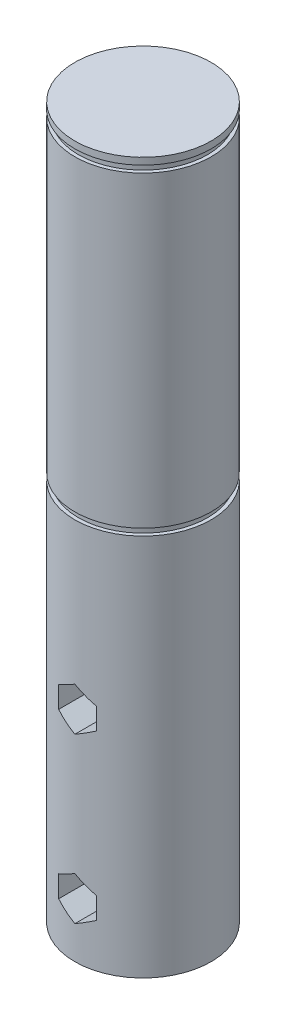
SolidWorks part; units mm, degrees
material "延性铁"
ref_plane "前视基准面" through (0, 0, 0) normal (0, 0, 1) x (1, 0, 0)
ref_plane "上视基准面" through (0, 0, 0) normal (0, 1, 0) x (1, 0, 0)
ref_plane "右视基准面" through (0, 0, 0) normal (1, 0, 0) x (0, 0, -1)
sketch "草图1" plane through (0, 0, 0) normal (0, 1, 0) x (1, 0, 0)
  circle A0 centre (5.9, 0) radius 9.975
  dimension "D1" = 19.95
extrude "凸台-拉伸1" add sketch "草图1" along normal blind 40
ref_plane "基准面1" through (0, 20, 0) normal (0, -1, 0) x (-1, 0, 0)
sketch "草图5" plane through (0, 40, 0) normal (0, 1, 0) x (1, 0, 0)
  circle A0 centre (5.9, 0) radius 9.975
  dimension "D1" = 19.95
extrude "16mm 铰链间距" add sketch "草图5" along normal blind 16
sketch "草图6" plane through (0, 56, 0) normal (0, 1, 0) x (1, 0, 0)
  circle A0 centre (5.9, 0) radius 9.45
  circle A1 centre (5.9, 0) radius 9.975 construction
  dimension "D1" = 18.9
extrude "卡簧1" add sketch "草图6" along normal blind 1
sketch "草图7" plane through (0, 57, 0) normal (0, 1, 0) x (1, 0, 0)
  circle A0 centre (5.9, 0) radius 9.975
  dimension "D1" = 19.95
extrude "凸台-拉伸4" add sketch "草图7" along normal blind 45
sketch "草图8" plane through (0, 102, 0) normal (0, 1, 0) x (1, 0, 0)
  circle A0 centre (5.9, 0) radius 9.45
  dimension "D1" = 18.9
extrude "卡簧2" add sketch "草图8" along normal blind 1
sketch "草图9" plane through (0, 103, 0) normal (0, 1, 0) x (1, 0, 0)
  circle A0 centre (5.9, 0) radius 9.975
  circle A1 centre (5.9, 0) radius 9.45 construction
  dimension "D1" = 19.95
extrude "凸台-拉伸6" add sketch "草图9" along normal blind 1
ref_plane "基准面2" through (0, 0, 9.975) normal (0, 0, 1) x (1, 0, 0)
sketch "草图10" plane through (0, 0, 9.975) normal (0, 0, 1) x (1, 0, 0)
  line L0 (5.9, 104) -> (5.9, 0) construction
  line L1 (15.875, 104) -> (-4.075, 104) construction
  line L2 (-4.075, 0) -> (15.875, 0) construction
  line L4 (8.65, 9.5877) -> (5.9, 11.1754)
  line L5 (5.9, 11.1754) -> (3.15, 9.5877)
  line L6 (3.15, 9.5877) -> (3.15, 6.4123)
  line L7 (3.15, 6.4123) -> (5.9, 4.8246)
  line L8 (5.9, 4.8246) -> (8.65, 6.4123)
  line L9 (8.65, 6.4123) -> (8.65, 9.5877)
  circle A0 centre (5.9, 8) radius 2.75 construction
  dimension "D2" = 5.5
  dimension "D1" = 8
extrude "切除-拉伸1" cut sketch "草图10" against normal blind 8
mirror "镜向2" about plane through (0, 20, 0) normal (0, -1, 0) of "切除-拉伸1"
